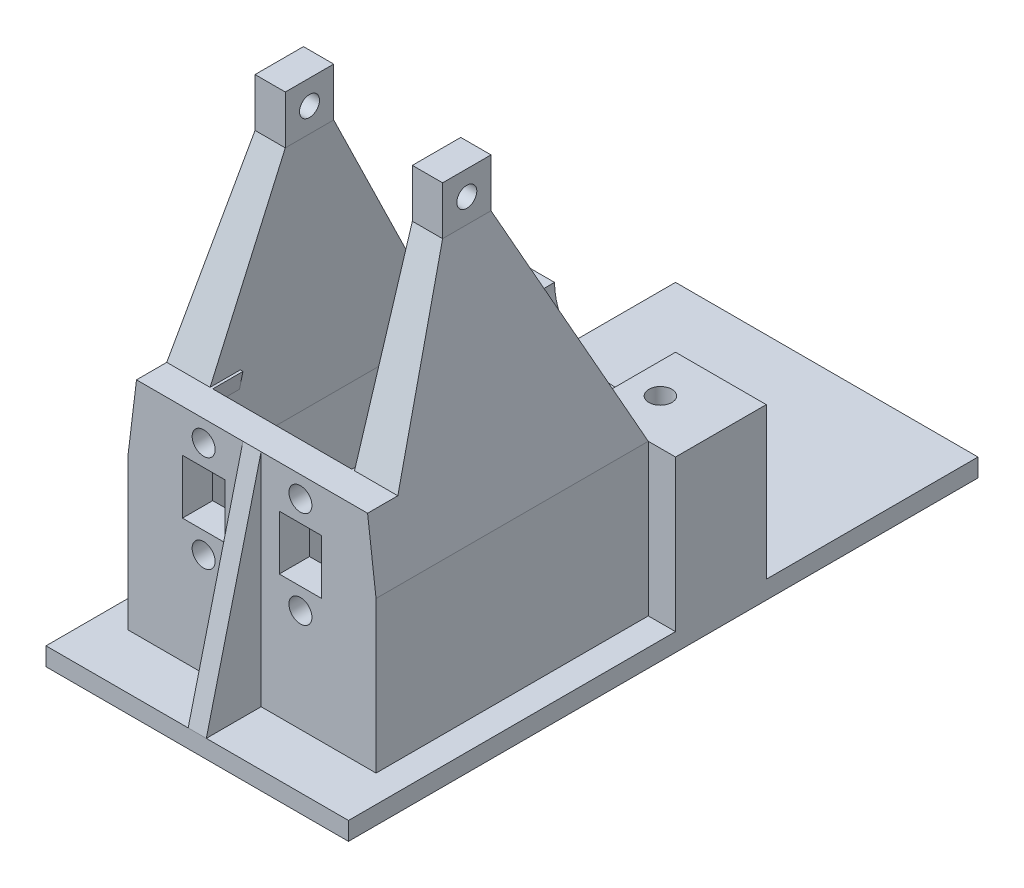
SolidWorks part; units mm, degrees
material "ABS"
ref_plane "Front Plane" through (0, 0, 0) normal (0, 0, 1) x (1, 0, 0)
ref_plane "Top Plane" through (0, 0, 0) normal (0, 1, 0) x (1, 0, 0)
ref_plane "Right Plane" through (0, 0, 0) normal (1, 0, 0) x (0, 0, -1)
sketch "Mouting Mount Sketch" plane through (0, 0, 0) normal (0, 0, 1) x (1, 0, 0)
  line L1 (25, -55) -> (-25, -55)
  line L2 (25, -55) -> (25, 0)
  line L3 (25, 0) -> (-25, 0)
  line L4 (-25, -55) -> (-25, 0)
  line L5 (25, -55) -> (-25, 0) construction
  line L6 (25, 0) -> (-25, -55) construction
  circle A0 centre (0, 0) radius 10
  point P3 (0, -27.5)
  dimension "D1" = 20
  dimension "D2" = 50
  dimension "D3" = 55
extrude "Motor Mount Solid" add sketch "Mouting Mount Sketch" along normal mid plane 15 contours A0 L3 L4 L1 L2
sketch "Encoder Distance Sketch" plane through (0, -55, 0) normal (0, -1, 0) x (1, 0, 0)
  line L0 (25, 7.5) -> (25, -7.5) construction
  line L1 (-25, 7.5) -> (25, 7.5)
  line L2 (-25, 7.5) -> (-25, 47.5)
  line L3 (-25, 47.5) -> (25, 47.5)
  line L4 (25, 7.5) -> (25, 47.5)
  line L5 (-25, -7.5) -> (25, -7.5) construction
  line L6 (-25, -7.5) -> (-25, 52.5) construction
  line L7 (-25, 52.5) -> (25, 52.5) construction
  line L8 (25, -7.5) -> (25, 52.5) construction
  line M9 (-25, -7.5) -> (25, -7.5)
  line M10 (25, -7.5) -> (25, 7.5)
  line M11 (25, 7.5) -> (-25, 7.5)
  line M12 (-25, 7.5) -> (-25, -7.5)
  dimension "D1" = 40
  dimension "D2" = 5
extrude "Encoder Distance Solid" add sketch "Encoder Distance Sketch" along normal blind 5 contours M12 M9 M10 M11 | L4 L3 L2 M11 | L3 L8 L7 L6
sketch "Encoder Mount Sketch" plane through (0, 0, 47.5) normal (0, 0, 1) x (1, 0, 0)
  line L0 (-25, -60) -> (-25, -55)
  line L1 (-8, -8) -> (8, -8) construction
  line L2 (-8, -8) -> (-8, 8) construction
  line L3 (-8, 8) -> (8, 8) construction
  line L4 (8, -8) -> (8, 8) construction
  line L5 (-8, -8) -> (8, 8) construction
  line L6 (-8, 8) -> (8, -8) construction
  line L7 (-11.5, -11.5) -> (11.5, -11.5) construction
  line L8 (-11.5, -11.5) -> (-11.5, 11.5) construction
  line L9 (-11.5, 11.5) -> (11.5, 11.5)
  line L10 (11.5, -11.5) -> (11.5, 11.5) construction
  line L11 (-11.5, -11.5) -> (11.5, 11.5) construction
  line L12 (-11.5, 11.5) -> (11.5, -11.5) construction
  line L13 (-11.5, 4.5) -> (-4.5, 4.5)
  line L14 (-11.5, 4.5) -> (-11.5, -4.5)
  line L15 (-11.5, -4.5) -> (-4.5, -4.5)
  line L16 (-4.5, 4.5) -> (-4.5, -4.5)
  line L17 (-11.5, 4.5) -> (-4.5, -4.5) construction
  line L18 (-11.5, -4.5) -> (-4.5, 4.5) construction
  line L19 (4.5, 4.5) -> (11.5, 4.5)
  line L20 (4.5, 4.5) -> (4.5, -4.5)
  line L21 (4.5, -4.5) -> (11.5, -4.5)
  line L22 (11.5, 4.5) -> (11.5, -4.5)
  line L23 (4.5, 4.5) -> (11.5, -4.5) construction
  line L24 (4.5, -4.5) -> (11.5, 4.5) construction
  line L25 (-25, -55) -> (-11.5, 11.5)
  line L26 (-25, -60) -> (25, -60)
  line L27 (25, -60) -> (25, -55)
  line L28 (25, -55) -> (11.5, 11.5)
  circle A0 centre (-8, 8) radius 1.9
  circle A1 centre (8, 8) radius 1.9
  circle A2 centre (-8, -8) radius 1.9
  circle A3 centre (8, -8) radius 1.9
  circle A4 centre (8, 8) radius 3.5 construction
  circle A5 centre (-8, 8) radius 3.5 construction
  circle A6 centre (-8, -8) radius 3.5 construction
  circle A7 centre (8, -8) radius 3.5 construction
  point P0 (0, 0)
  point P14 (0, 0)
  point P19 (-8, 0)
  point P24 (8, 0)
  dimension "D2" = 3.8
  dimension "D3" = 7
  dimension "D1" = 16
extrude "Encoder Mount Solid" add sketch "Encoder Mount Sketch" along normal blind 5
sketch "Motor Clamp Mounting Holes Sketch" plane through (0, 0, 0) normal (0, 1, 0) x (1, 0, 0)
  line L0 (-15, 0) -> (15, 0) construction
  circle A0 centre (-15, 0) radius 1.9
  circle A1 centre (15, 0) radius 1.9
  point P4 (0, 0)
  dimension "D2" = 3.8
  dimension "D1" = 30
extrude "Motor Clamp Mounting Holes Cut" cut sketch "Motor Clamp Mounting Holes Sketch" against normal blind 16
sketch "Gusset Plate Sketch" plane through (0, 0, 52.5) normal (0, 0, 1) x (1, 0, 0)
  line L1 (-25, -55) -> (25, -55)
  line L2 (-25, -55) -> (-25, -60)
  line L3 (-25, -60) -> (25, -60)
  line L4 (25, -55) -> (25, -60)
extrude "Gusset Plate Solid" add sketch "Gusset Plate Sketch" along normal blind 16.5
sketch "Gusset Sketch" plane through (0, 0, 0) normal (1, 0, 0) x (0, 0, -1)
  line L0 (-52.5, 11.5) -> (-69, -55)
  line L1 (-69, -55) -> (-52.5, -55)
  line L2 (-52.5, -55) -> (-52.5, 11.5)
extrude "Gusset Solid" add sketch "Gusset Sketch" along normal mid plane 3
sketch "Mounting Plate Sketch" plane through (0, -55, 0) normal (0, 1, 0) x (1, 0, 0)
  line L0 (25, -7.5) -> (25, -47.5) construction
  line L1 (-25, -69) -> (25, -69)
  line L2 (-25, -69) -> (-25, 23)
  line L3 (-25, 23) -> (25, 23)
  line L4 (25, -69) -> (25, 23)
  line L5 (-19, -63) -> (19, -63) construction
  line L6 (-19, 17) -> (19, 17) construction
  circle A0 centre (-19, -63) radius 2.65
  circle A1 centre (19, -63) radius 6 construction
  circle A2 centre (19, -63) radius 2.65
  circle A3 centre (-19, -63) radius 6 construction
  circle A4 centre (-19, 17) radius 6 construction
  circle A5 centre (19, 17) radius 6 construction
  circle A6 centre (-19, 17) radius 2.65
  circle A7 centre (19, 17) radius 2.65
  point P10 (0, -63)
  point P18 (0, 17)
  dimension "D1" = 12
  dimension "D2" = 5.3
  dimension "D3" = 80
extrude "Mounting Plate Solid" add sketch "Mounting Plate Sketch" against normal up to surface (5 mm away) up to face at (0, -60, 30.75)
sketch "Mounting Hole Sketch" plane through (0, -55, 0) normal (0, 1, 0) x (1, 0, 0)
  line L0 (25, 23) -> (25, -69) construction
  line L3 (25, -23) -> (-25, -23) construction
  line L4 (-25, -47.5) -> (-25, -7.5) construction
  circle A0 centre (-19, 17) radius 2.65
  circle A1 centre (19, 17) radius 2.65
  circle A3 centre (19, -63) radius 2.65
  circle A4 centre (-19, -63) radius 2.65
  circle A5 centre (-19, 17) radius 2.65 construction
extrude "Mounting Holes Cut" cut sketch "Mounting Hole Sketch" against normal through all both and the other way through all contours A3 | A4 | A1 | A0
sketch "Mounting Plate Trim Sketch" plane through (0, -55, 0) normal (0, 1, 0) x (1, 0, 0)
  line L1 (-25, 23) -> (25, 23)
  line L2 (-25, 23) -> (-25, 7.5)
  line L3 (-25, 7.5) -> (25, 7.5)
  line L4 (25, 23) -> (25, 7.5)
  line L5 (-25, -7.5) -> (25, -7.5)
  line L6 (-25, -7.5) -> (-25, -47.5)
  line L7 (-25, -47.5) -> (25, -47.5)
  line L8 (25, -7.5) -> (25, -47.5)
  line L9 (1.5, -52.5) -> (25, -52.5)
  line L10 (1.5, -52.5) -> (1.5, -69)
  line L11 (1.5, -69) -> (25, -69)
  line L12 (25, -52.5) -> (25, -69)
  line L13 (-1.5, -52.5) -> (-25, -52.5)
  line L14 (-1.5, -52.5) -> (-1.5, -69)
  line L15 (-1.5, -69) -> (-25, -69)
  line L16 (-25, -52.5) -> (-25, -69)
extrude "Mounting Plate Trim Cut" cut sketch "Mounting Plate Trim Sketch" against normal blind 2
sketch "Sketch1" plane through (-25, 0, 0) normal (-1, 0, 0) x (0, 0, 1)
  line L0 (7.5, -57) -> (7.5, 0) construction
  line L1 (-7.5, 25) -> (7.5, 25) construction
  line L2 (-7.5, 25) -> (-7.5, -25) construction
  line L3 (-7.5, -25) -> (7.5, -25) construction
  line L4 (7.5, 25) -> (7.5, -25) construction
  line L5 (-7.5, 25) -> (7.5, -25) construction
  line L6 (-7.5, -25) -> (7.5, 25) construction
  line L8 (-23, -60) -> (69, -60)
  line L9 (-23, -60) -> (-23, -25)
  line L10 (-23, -25) -> (69, -25)
  line L11 (69, -60) -> (69, -25)
  point P0 (0, 0)
  point P13 (69, -60)
  dimension "D1" = 50
extrude "Cut-Extrude1" cut sketch "Sketch1" against normal through all both
sketch "Sketch2" plane through (0, -25, 0) normal (0, -1, 0) x (1, 0, 0)
  line L1 (-25, 61.5564) -> (25, 61.5564)
  line L2 (-25, 61.5564) -> (-25, -42.5)
  line L3 (-25, -42.5) -> (25, -42.5)
  line L4 (25, 61.5564) -> (25, -42.5)
  line L5 (-1.5, 61.5564) -> (1.5, 61.5564) construction
  line L6 (25, -7.5) -> (-25, -7.5) construction
  line L7 (-25, 7.5) -> (-25, -7.5) construction
  point P5 (-25, -7.5)
  point P9 (0, 0)
  point P10 (0, 0)
  point P13 (-19.6293, -57.5)
  dimension "D1" = 50
  dimension "D2" = 35
extrude "Boss-Extrude1" add sketch "Sketch2" along normal blind 3
sketch "Sketch3" plane through (0, -25, 0) normal (0, 1, 0) x (1, 0, 0)
  line L0 (12.5, -32.5) -> (-12.5, -32.5) construction
  line L1 (-25, -47.5) -> (-12.5, -47.5) construction
  line L2 (-25, -47.5) -> (-25, -7.5) construction
  line L3 (-25, -7.5) -> (-12.5, -7.5) construction
  line L4 (-12.5, -47.5) -> (-12.5, -7.5) construction
  line L5 (-25, -47.5) -> (-12.5, -7.5) construction
  line L6 (-25, -7.5) -> (-12.5, -47.5) construction
  line L7 (25, -47.5) -> (12.5, -47.5) construction
  line L8 (25, -47.5) -> (25, -7.5) construction
  line L9 (25, -7.5) -> (12.5, -7.5) construction
  line L10 (12.5, -47.5) -> (12.5, -7.5) construction
  line L11 (25, -47.5) -> (12.5, -7.5) construction
  line L12 (25, -7.5) -> (12.5, -47.5) construction
  line L13 (18.9098, -47.5) -> (11.5, -47.5) construction
  line L14 (-11.5, -47.5) -> (-18.9098, -47.5) construction
  line L15 (-10, -7.5) -> (-25, -7.5) construction
  line L16 (25, -7.5) -> (10, -7.5) construction
  line L17 (25, -7.5) -> (25, -61.5564) construction
  line L19 (4.5, -28.5) -> (-4.5, -28.5) construction
  line L20 (4.5, -28.5) -> (4.5, -36.5) construction
  line L21 (4.5, -36.5) -> (-4.5, -36.5) construction
  line L22 (-4.5, -28.5) -> (-4.5, -36.5) construction
  line L23 (4.5, -28.5) -> (-4.5, -36.5) construction
  line L24 (4.5, -36.5) -> (-4.5, -28.5) construction
  line L25 (12.5, -47.5) -> (20.5, -47.5)
  line L26 (12.5, -47.5) -> (12.5, -7.5)
  line L27 (12.5, -7.5) -> (20.5, -7.5)
  line L28 (20.5, -47.5) -> (20.5, -7.5)
  line L29 (-12.5, -47.5) -> (-20.5, -47.5)
  line L30 (-12.5, -47.5) -> (-12.5, -7.5)
  line L31 (-12.5, -7.5) -> (-20.5, -7.5)
  line L32 (-20.5, -47.5) -> (-20.5, -7.5)
  point P0 (-18.75, -27.5)
  point P5 (18.75, -27.5)
  point P13 (0, -32.5)
  point P34 (0, -32.5)
  dimension "D1" = 25
  dimension "D2" = 5
  dimension "D3" = 9
  dimension "D4" = 8
  dimension "D5" = 8
extrude "Boss-Extrude2" add sketch "Sketch3" along normal up to surface (25 mm away) up to face at (13.1, 0, 0)
sketch "Sketch4" plane through (0, 0, 47.5) normal (0, 0, 1) x (1, 0, 0)
  line L0 (0, 0) -> (0, 45) construction
  line L1 (-20.5, 0) -> (-15.5, 41)
  line L2 (4.5, 37.5) -> (-4.5, 37.5) construction
  line L3 (4.5, 37.5) -> (4.5, 52.5) construction
  line L4 (4.5, 52.5) -> (-4.5, 52.5) construction
  line L5 (-4.5, 37.5) -> (-4.5, 52.5) construction
  line L6 (4.5, 37.5) -> (-4.5, 52.5) construction
  line L7 (4.5, 52.5) -> (-4.5, 37.5) construction
  line L8 (-4.5, 42.75) -> (-5.5, 42.75) construction
  line L9 (-4.5, 42.75) -> (-4.5, 47.25) construction
  line L10 (-4.5, 47.25) -> (-5.5, 47.25) construction
  line L11 (-5.5, 42.75) -> (-5.5, 47.25) construction
  line L12 (-4.5, 42.75) -> (-5.5, 47.25) construction
  line L13 (-4.5, 47.25) -> (-5.5, 42.75) construction
  line L14 (-5.5, 41) -> (-10.5, 41) construction
  line L15 (-5.5, 41) -> (-5.5, 49) construction
  line L16 (-5.5, 49) -> (-10.5, 49) construction
  line L17 (-10.5, 41) -> (-10.5, 49)
  line L18 (-5.5, 41) -> (-10.5, 49) construction
  line L19 (-5.5, 49) -> (-10.5, 41) construction
  line L20 (-10.5, 41) -> (-15.5, 41) construction
  line L21 (-10.5, 41) -> (-10.5, 49) construction
  line L22 (-10.5, 49) -> (-15.5, 49)
  line L23 (-15.5, 41) -> (-15.5, 49)
  line L24 (-10.5, 41) -> (-15.5, 49) construction
  line L25 (-10.5, 49) -> (-15.5, 41) construction
  line L26 (-12.5, 0) -> (-10.5, 41)
  line L27 (-12.5, 0) -> (-20.5, 0)
  line L28 (-10.5, 41) -> (-15.5, 41) construction
  line L33 (10.5, 41) -> (10.5, 49)
  line L34 (12.5, 0) -> (10.5, 41)
  line L35 (12.5, 0) -> (20.5, 0)
  line L36 (20.5, 0) -> (15.5, 41)
  line L37 (15.5, 41) -> (15.5, 49)
  line L38 (10.5, 49) -> (15.5, 49)
  point P7 (-5, 45)
  point P12 (-8, 45)
  point P18 (-13, 45)
  dimension "D1" = 45
  dimension "D2" = 9
  dimension "D3" = 1
  dimension "D4" = 4.5
  dimension "D5" = 8
  dimension "D6" = 15
  dimension "D7" = 31
  dimension "D8" = 5
extrude "Boss-Extrude3" add sketch "Sketch4" against normal up to surface (40 mm away) contours L26 L28 L1 L27
sketch "Sketch5" plane through (-15.5, 0, 0) normal (-1, 0, 0) x (0, 0, 1)
  line L0 (7.5, 45) -> (47.5, 45) construction
  line L1 (7.5, 41) -> (7.5, 49) construction
  line L2 (47.5, 49) -> (47.5, 41) construction
  line L3 (27.5, 49) -> (27.5, -28) construction
  line L4 (7.5, 49) -> (47.5, 49) construction
  line L5 (61.5564, -28) -> (-42.5, -28) construction
  circle A0 centre (32.5, 45) radius 1.65
  point P14 (0, 0)
  dimension "D2" = 3.3
  dimension "D1" = 5
extrude "Cut-Extrude2" cut sketch "Sketch5" against normal through all both and the other way through all
sketch "Sketch6" plane through (-15.5, 0, 0) normal (-1, 0, 0) x (0, 0, 1)
  line L0 (7.5, 49) -> (47.5, 49) construction
  line L1 (28.5, 41) -> (36.5, 41) construction
  line L2 (28.5, 41) -> (28.5, 49) construction
  line L3 (28.5, 49) -> (36.5, 49) construction
  line L4 (36.5, 41) -> (36.5, 49) construction
  line L5 (28.5, 41) -> (36.5, 49) construction
  line L6 (28.5, 49) -> (36.5, 41) construction
  line L7 (36.5, 41) -> (47.5, 11.5)
  line L8 (47.5, 11.5) -> (52.5, 11.5)
  line L9 (52.5, 11.5) -> (52.5, 49)
  line L10 (52.5, 49) -> (36.5, 49)
  line L11 (36.5, 49) -> (36.5, 41)
  line L12 (7.5, 0) -> (28.5, 41)
  line L13 (28.5, 41) -> (28.5, 49)
  line L14 (28.5, 49) -> (7.5, 49)
  line L15 (7.5, 49) -> (7.5, 0)
  point P0 (32.5, 45)
extrude "Cut-Extrude3" cut sketch "Sketch6" against normal through all both and the other way through all
sketch "Sketch7" plane through (0, 0, 52.5) normal (0, 0, 1) x (1, 0, 0)
  line L0 (-11.5, 11.5) -> (-19.0976, 11.5)
  line L2 (-18.9098, -25) -> (-11.5, 11.5)
  line L3 (11.5, 11.5) -> (18.9098, -25)
  line L5 (19.0976, 11.5) -> (11.5, 11.5)
  line L6 (-19.0976, 11.5) -> (-20.5, 0)
  line L7 (-20.5, 0) -> (-20.5, -25)
  line L8 (-20.5, -25) -> (-18.9098, -25)
  line L9 (19.0976, 11.5) -> (20.5, 0)
  line L10 (20.5, 0) -> (20.5, -25)
  line L11 (20.5, -25) -> (18.9098, -25)
  line L12 (19.0976, 11.5) -> (15.5, 41) construction
extrude "Boss-Extrude4" add sketch "Sketch7" against normal blind 10
